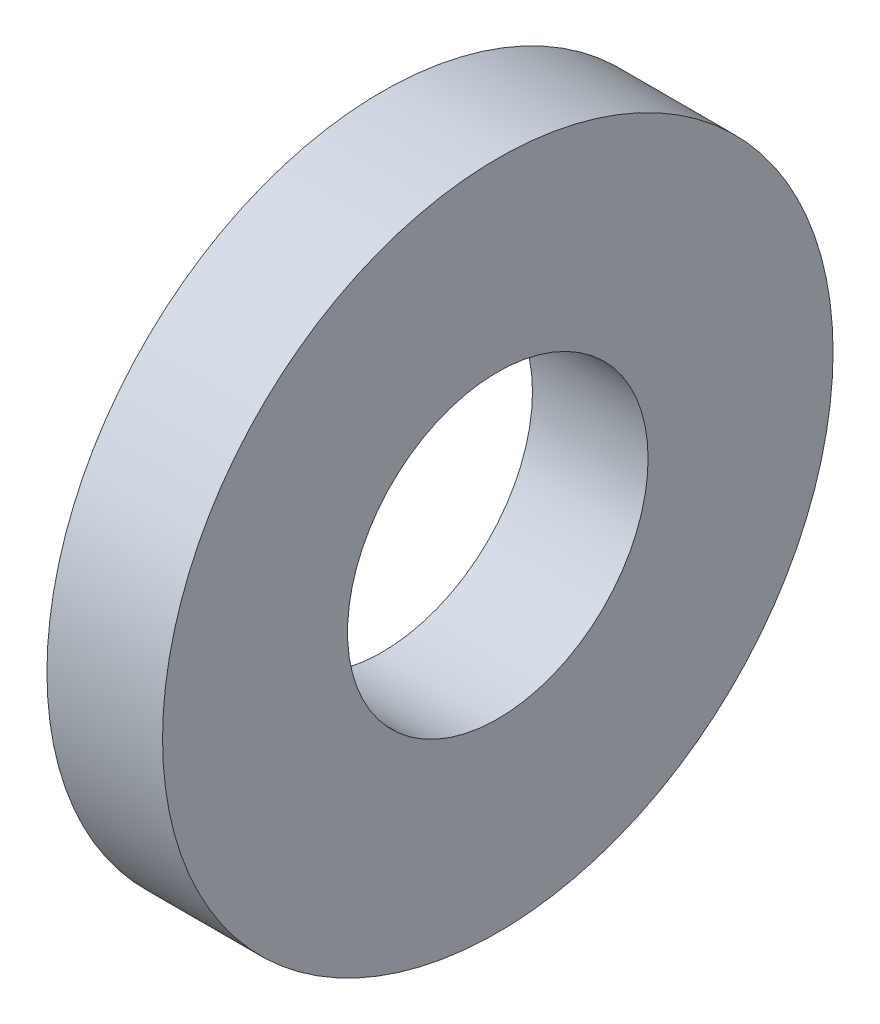
SolidWorks part; units mm, degrees
ref_plane "Alzado" through (0, 0, 0) normal (0, 0, 1) x (1, 0, 0)
ref_plane "Planta" through (0, 0, 0) normal (0, 1, 0) x (1, 0, 0)
ref_plane "Vista lateral" through (0, 0, 0) normal (1, 0, 0) x (0, 0, -1)
sketch "Croquis2" plane through (0, 0, 0) normal (1, 0, 0) x (0, 0, -1)
  circle A0 centre (0, 0) radius 3.25
  circle A1 centre (0, 0) radius 7.25
  dimension "D1" = 4
  dimension "D2" = 6.5
extrude "Saliente-Extruir1" add sketch "Croquis2" along normal mid plane 2.5
